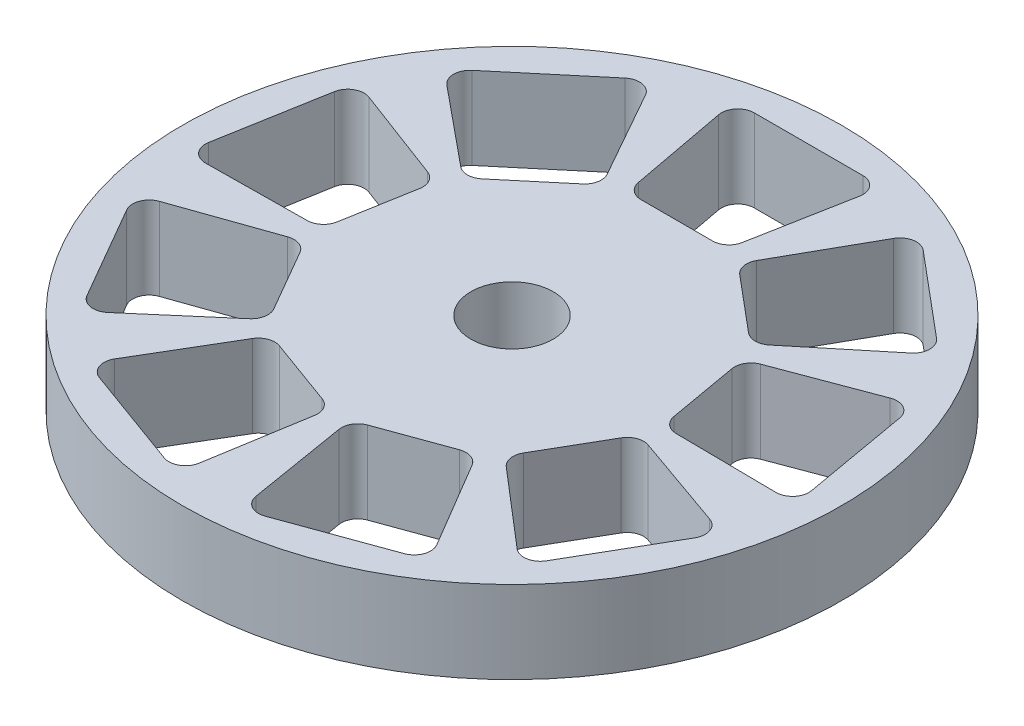
SolidWorks part; units mm, degrees
ref_plane "Front Plane" through (0, 0, 0) normal (0, 0, 1) x (1, 0, 0)
ref_plane "Top Plane" through (0, 0, 0) normal (0, 1, 0) x (1, 0, 0)
ref_plane "Right Plane" through (0, 0, 0) normal (1, 0, 0) x (0, 0, -1)
sketch "Sketch1" plane through (0, 0, 0) normal (0, 1, 0) x (1, 0, 0)
  circle A0 centre (0, 0) radius 101.6
  dimension "D1" = 203.2
extrude "Boss-Extrude1" add sketch "Sketch1" along normal blind 25.4
sketch "Sketch2" plane through (0, 25.4, 0) normal (0, 1, 0) x (1, 0, 0)
  line L0 (0, 0) -> (0, 101.6) construction
  line L1 (0, 91.44) -> (16.739, 91.44)
  line L2 (0, 50.8) -> (11.024, 50.8)
  line L3 (16.017, 54.9438) -> (21.732, 85.4238)
  line L4 (0, 50.8) -> (-11.024, 50.8)
  line L5 (0, 91.44) -> (-16.739, 91.44)
  line L6 (-21.732, 85.4238) -> (-16.017, 54.9438)
  line L7 (38.2617, 79.4075) -> (23.0475, 52.3849)
  line L8 (32.6536, 38.9151) -> (24.2088, 46.0011)
  line L9 (32.6536, 38.9151) -> (41.0985, 31.829)
  line L10 (47.5869, 31.7939) -> (71.557, 51.4694)
  line L11 (58.7765, 70.0471) -> (71.5993, 59.2875)
  line L12 (58.7765, 70.0471) -> (45.9537, 80.8067)
  line L13 (80.3523, 36.2355) -> (51.3278, 25.3145)
  line L14 (50.0282, 8.8213) -> (48.1139, 19.6778)
  line L15 (50.0282, 8.8213) -> (51.9425, -2.0352)
  line L16 (56.8904, -6.2327) -> (87.8998, -6.5681)
  line L17 (90.0508, 15.8784) -> (92.9575, -0.6063)
  line L18 (90.0508, 15.8784) -> (87.1441, 32.3631)
  line L19 (84.8452, -23.8915) -> (55.5912, -13.6008)
  line L20 (43.9941, -25.4) -> (49.5061, -15.853)
  line L21 (43.9941, -25.4) -> (38.4821, -34.947)
  line L22 (39.5743, -41.343) -> (63.1132, -61.5323)
  line L23 (79.1894, -45.72) -> (70.8199, -60.2164)
  line L24 (79.1894, -45.72) -> (87.5589, -31.2236)
  line L25 (49.638, -72.8394) -> (33.8429, -46.1522)
  line L26 (17.3746, -47.7364) -> (27.7338, -43.966)
  line L27 (17.3746, -47.7364) -> (7.0155, -51.5068)
  line L28 (3.7409, -57.1084) -> (8.7953, -87.7049)
  line L29 (31.2743, -85.9255) -> (15.5448, -91.6506)
  line L30 (31.2743, -85.9255) -> (47.0038, -80.2004)
  line L31 (-8.7953, -87.7049) -> (-3.7409, -57.1084)
  line L32 (-17.3746, -47.7364) -> (-7.0155, -51.5068)
  line L33 (-17.3746, -47.7364) -> (-27.7338, -43.966)
  line L34 (-33.8429, -46.1522) -> (-49.638, -72.8394)
  line L35 (-31.2743, -85.9255) -> (-47.0038, -80.2004)
  line L36 (-31.2743, -85.9255) -> (-15.5448, -91.6506)
  line L37 (-63.1132, -61.5323) -> (-39.5743, -41.343)
  line L38 (-43.9941, -25.4) -> (-38.4821, -34.947)
  line L39 (-43.9941, -25.4) -> (-49.5061, -15.853)
  line L40 (-55.5912, -13.6008) -> (-84.8452, -23.8915)
  line L41 (-79.1894, -45.72) -> (-87.5589, -31.2236)
  line L42 (-79.1894, -45.72) -> (-70.8199, -60.2164)
  line L43 (-87.8998, -6.5681) -> (-56.8904, -6.2327)
  line L44 (-50.0282, 8.8213) -> (-51.9425, -2.0352)
  line L45 (-50.0282, 8.8213) -> (-48.1139, 19.6778)
  line L46 (-51.3278, 25.3145) -> (-80.3523, 36.2355)
  line L47 (-90.0508, 15.8784) -> (-87.1441, 32.3631)
  line L48 (-90.0508, 15.8784) -> (-92.9575, -0.6063)
  line L49 (-71.557, 51.4694) -> (-47.5869, 31.7939)
  line L50 (-32.6536, 38.9151) -> (-41.0985, 31.829)
  line L51 (-32.6536, 38.9151) -> (-24.2088, 46.0011)
  line L52 (-23.0475, 52.3849) -> (-38.2617, 79.4075)
  line L53 (-58.7765, 70.0471) -> (-45.9537, 80.8067)
  line L54 (-58.7765, 70.0471) -> (-71.5993, 59.2875)
  arc A0 (-21.732, 85.4238) -> (-16.739, 91.44) centre (-16.739, 86.36) cw
  circle A1 centre (0, 0) radius 91.44 construction
  circle A2 centre (0, 0) radius 50.8 construction
  arc A3 (16.739, 91.44) -> (21.732, 85.4238) centre (16.739, 86.36) cw
  arc A4 (16.017, 54.9438) -> (11.024, 50.8) centre (11.024, 55.88) cw
  arc A5 (-16.017, 54.9438) -> (-11.024, 50.8) centre (-11.024, 55.88) ccw
  circle A6 centre (0, 0) radius 50.8 construction
  arc A7 (23.0475, 52.3849) -> (24.2088, 46.0011) centre (27.4741, 49.8926) ccw
  arc A8 (38.2617, 79.4075) -> (45.9537, 80.8067) centre (42.6883, 76.9152) cw
  arc A9 (47.5869, 31.7939) -> (41.0985, 31.829) centre (44.3638, 35.7205) cw
  arc A10 (71.5993, 59.2875) -> (71.557, 51.4694) centre (68.3339, 55.396) cw
  circle A11 centre (0, 0) radius 50.8 construction
  arc A12 (51.3278, 25.3145) -> (48.1139, 19.6778) centre (53.1168, 20.56) ccw
  arc A13 (80.3523, 36.2355) -> (87.1441, 32.3631) centre (82.1413, 31.4809) cw
  arc A14 (56.8904, -6.2327) -> (51.9425, -2.0352) centre (56.9454, -1.153) cw
  arc A15 (92.9575, -0.6063) -> (87.8998, -6.5681) centre (87.9547, -1.4884) cw
  circle A16 centre (0, 0) radius 50.8 construction
  arc A17 (55.5912, -13.6008) -> (49.5061, -15.853) centre (53.9055, -18.393) ccw
  arc A18 (84.8452, -23.8915) -> (87.5589, -31.2236) centre (83.1594, -28.6836) cw
  arc A19 (39.5743, -41.343) -> (38.4821, -34.947) centre (42.8815, -37.487) cw
  arc A20 (70.8199, -60.2164) -> (63.1132, -61.5323) centre (66.4205, -57.6764) cw
  circle A21 centre (0, 0) radius 50.8 construction
  arc A22 (33.8429, -46.1522) -> (27.7338, -43.966) centre (29.4712, -48.7396) ccw
  arc A23 (49.638, -72.8394) -> (47.0038, -80.2004) centre (45.2664, -75.4268) cw
  arc A24 (3.7409, -57.1084) -> (7.0155, -51.5068) centre (8.7529, -56.2804) cw
  arc A25 (15.5448, -91.6506) -> (8.7953, -87.7049) centre (13.8074, -86.8769) cw
  circle A26 centre (0, 0) radius 50.8 construction
  arc A27 (-3.7409, -57.1084) -> (-7.0155, -51.5068) centre (-8.7529, -56.2804) ccw
  arc A28 (-8.7953, -87.7049) -> (-15.5448, -91.6506) centre (-13.8074, -86.8769) cw
  arc A29 (-33.8429, -46.1522) -> (-27.7338, -43.966) centre (-29.4712, -48.7396) cw
  arc A30 (-47.0038, -80.2004) -> (-49.638, -72.8394) centre (-45.2664, -75.4268) cw
  circle A31 centre (0, 0) radius 50.8 construction
  arc A32 (-39.5743, -41.343) -> (-38.4821, -34.947) centre (-42.8815, -37.487) ccw
  arc A33 (-63.1132, -61.5323) -> (-70.8199, -60.2164) centre (-66.4205, -57.6764) cw
  arc A34 (-55.5912, -13.6008) -> (-49.5061, -15.853) centre (-53.9055, -18.393) cw
  arc A35 (-87.5589, -31.2236) -> (-84.8452, -23.8915) centre (-83.1594, -28.6836) cw
  circle A36 centre (0, 0) radius 50.8 construction
  arc A37 (-56.8904, -6.2327) -> (-51.9425, -2.0352) centre (-56.9454, -1.153) ccw
  arc A38 (-87.8998, -6.5681) -> (-92.9575, -0.6063) centre (-87.9547, -1.4884) cw
  arc A39 (-51.3278, 25.3145) -> (-48.1139, 19.6778) centre (-53.1168, 20.56) cw
  arc A40 (-87.1441, 32.3631) -> (-80.3523, 36.2355) centre (-82.1413, 31.4809) cw
  circle A41 centre (0, 0) radius 50.8 construction
  arc A42 (-47.5869, 31.7939) -> (-41.0985, 31.829) centre (-44.3638, 35.7205) ccw
  arc A43 (-71.557, 51.4694) -> (-71.5993, 59.2875) centre (-68.3339, 55.396) cw
  arc A44 (-23.0475, 52.3849) -> (-24.2088, 46.0011) centre (-27.4741, 49.8926) cw
  arc A45 (-45.9537, 80.8067) -> (-38.2617, 79.4075) centre (-42.6883, 76.9152) cw
  point P15 (-22.86, 91.44)
  point P18 (22.86, 91.44)
  point P21 (15.24, 50.8)
  point P24 (-15.24, 50.8)
  point P148 (0, 0)
  dimension "D1" = 22.86
  dimension "D5" = 5.08
  dimension "D6" = 5.08
  dimension "D7" = 5.08
  dimension "D8" = 5.08
  dimension "D2" = 15.24
  dimension "D3" = 22.86
  dimension "D4" = 15.24
  dimension "D9" = 9
extrude "Cut-Extrude1" cut sketch "Sketch2" against normal blind 25.4
sketch "Sketch3" plane through (0, 25.4, 0) normal (0, 1, 0) x (1, 0, 0)
  circle A0 centre (0, 0) radius 12.7
extrude "Cut-Extrude2" cut sketch "Sketch3" against normal blind 25.4
